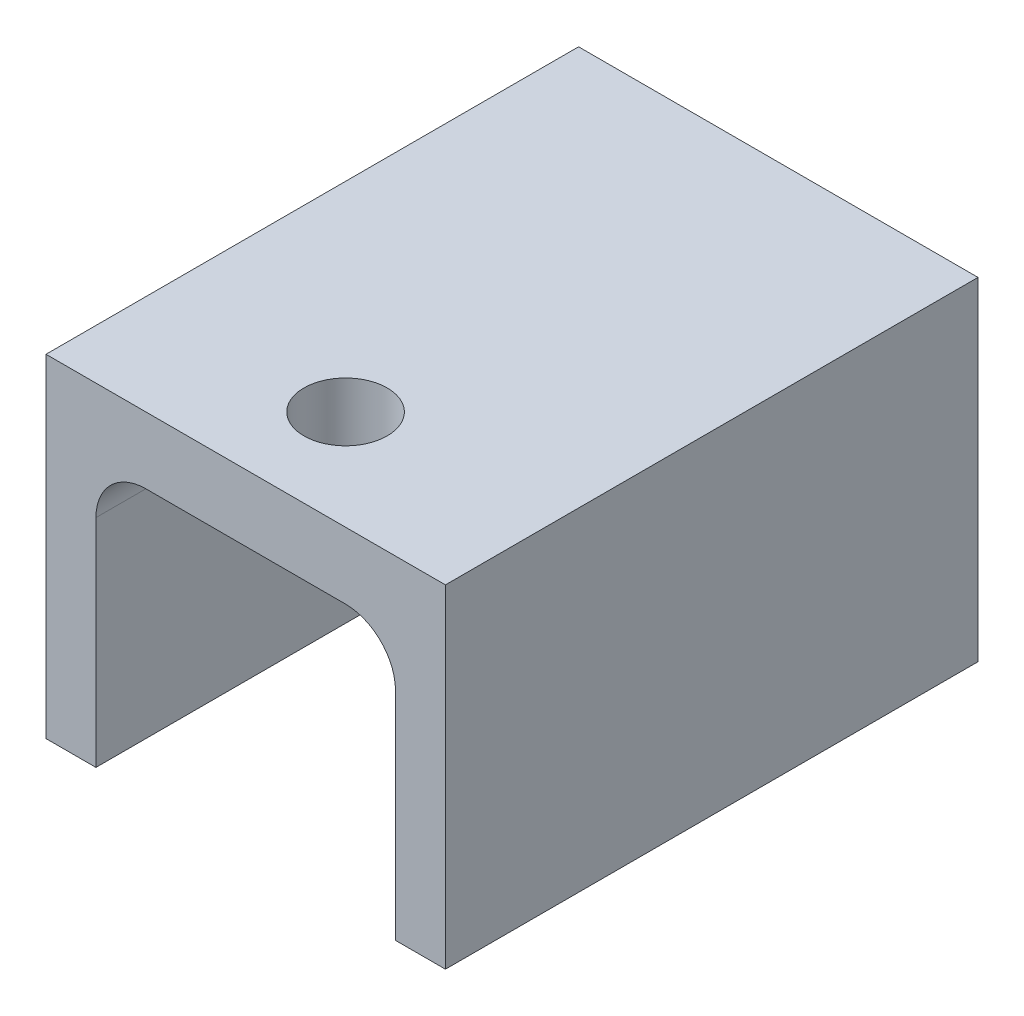
SolidWorks part; units mm, degrees
ref_plane "前视基准面" through (0, 0, 0) normal (0, 0, 1) x (1, 0, 0)
ref_plane "上视基准面" through (0, 0, 0) normal (0, 1, 0) x (1, 0, 0)
ref_plane "右视基准面" through (0, 0, 0) normal (1, 0, 0) x (0, 0, -1)
sketch "草图1" plane through (0, 0, 0) normal (0, 0, 1) x (1, 0, 0)
  line L1 (-9, 10) -> (9, 10)
  line L2 (-9, 10) -> (-9, -10)
  line L3 (-9, -10) -> (9, -10)
  line L4 (9, 10) -> (9, -10)
  line L5 (-9, 10) -> (9, -10) construction
  line L6 (-9, -10) -> (9, 10) construction
  point P0 (0, 0)
  dimension "D1" = 20
  dimension "D2" = 18
extrude "凸台-拉伸1" add sketch "草图1" along normal blind 4
sketch "草图2" plane through (0, 0, 4) normal (0, 0, 1) x (1, 0, 0)
  line L1 (-9, 10) -> (9, 10)
  line L2 (-9, 10) -> (-9, 6)
  line L3 (-9, 6) -> (9, 6)
  line L4 (9, 10) -> (9, 6)
  line L5 (9, -10) -> (9, 10) construction
  dimension "D1" = 4
  dimension "D2" = 18
extrude "凸台-拉伸2" add sketch "草图2" along normal blind 28
sketch "草图3" plane through (0, 6, 0) normal (0, -1, 0) x (1, 0, 0)
  circle A0 centre (0, 26) radius 2.5
  dimension "D1" = 5
  dimension "D2" = 26
extrude "切除-拉伸1" cut sketch "草图3" against normal through all
sketch "草图4" plane through (0, 0, 4) normal (0, 0, 1) x (1, 0, 0)
  line L0 (-9, -10) -> (9, -10) construction
  line L1 (-6, -0.25) -> (6, -0.25) construction
  line L2 (-6, -0.25) -> (-6, -6.75) construction
  line L3 (-6, -6.75) -> (6, -6.75) construction
  line L4 (6, -0.25) -> (6, -6.75) construction
  line L5 (-6, -0.25) -> (6, -6.75) construction
  line L6 (-6, -6.75) -> (6, -0.25) construction
  circle A0 centre (-6, -0.25) radius 1.5
  circle A1 centre (-6, -6.75) radius 1.5
  circle A2 centre (6, -0.25) radius 1.5
  circle A3 centre (6, -6.75) radius 1.5
  point P0 (0, -3.5)
  dimension "D3" = 3
  dimension "D4" = 3
  dimension "D5" = 3
  dimension "D6" = 3
  dimension "D1" = 6.5
  dimension "D2" = 12
  dimension "D7" = 6.5
extrude "切除-拉伸2" cut sketch "草图4" against normal blind 32
sketch "草图5" plane through (9, 0, 0) normal (1, 0, 0) x (0, 0, -1)
  line L0 (-32, 10) -> (0, 10)
  line L1 (0, 10) -> (0, -10)
  line L2 (0, -10) -> (-4, -10)
  line L3 (-4, -10) -> (-32, 6)
  line L4 (-32, 6) -> (-32, 10)
extrude "凸台-拉伸3" add sketch "草图5" along normal blind 3
sketch "草图6" plane through (-9, 0, 0) normal (-1, 0, 0) x (0, 0, 1)
  line L0 (0, -10) -> (0, 10)
  line L1 (0, 10) -> (32, 10)
  line L2 (32, 10) -> (32, 6)
  line L3 (32, 6) -> (4, -10)
  line L4 (4, -10) -> (0, -10)
extrude "凸台-拉伸4" add sketch "草图6" along normal blind 3
sketch "草图7" plane through (-12, 0, 0) normal (-1, 0, 0) x (0, 0, 1)
  line L0 (32, 6) -> (4, -10)
  line L1 (4, -10) -> (32, -10)
  line L2 (32, -10) -> (32, 6)
  dimension "D1" = 28
extrude "凸台-拉伸5" add sketch "草图7" against normal blind 3
sketch "草图8" plane through (12, 0, 0) normal (1, 0, 0) x (0, 0, -1)
  line L0 (-32, 6) -> (-4, -10)
  line L1 (-4, -10) -> (-32, -10)
  line L2 (-32, -10) -> (-32, 6)
extrude "凸台-拉伸6" add sketch "草图8" against normal blind 3
fillet "圆角1" radius 3 2 edges at (-9, 6, 18) (9, 6, 18)
